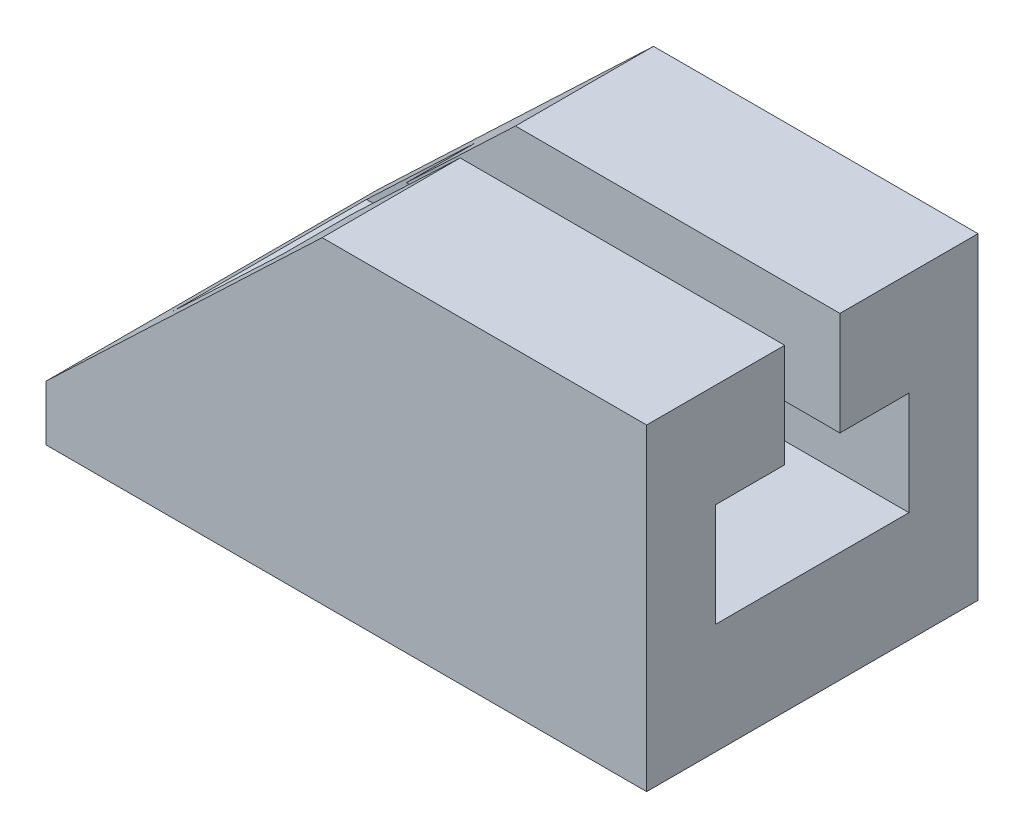
SolidWorks part; units mm, degrees
ref_plane "Front Plane" through (0, 0, 0) normal (0, 0, 1) x (1, 0, 0)
ref_plane "Top Plane" through (0, 0, 0) normal (0, 1, 0) x (1, 0, 0)
ref_plane "Right Plane" through (0, 0, 0) normal (1, 0, 0) x (0, 0, -1)
sketch "Sketch1" plane through (0, 0, 0) normal (0, 1, 0) x (1, 0, 0)
  line L1 (-43.5, -24) -> (43.5, -24)
  line L2 (-43.5, -24) -> (-43.5, 24)
  line L3 (-43.5, 24) -> (43.5, 24)
  line L4 (43.5, -24) -> (43.5, 24)
  line L5 (-43.5, -24) -> (43.5, 24) construction
  line L6 (-43.5, 24) -> (43.5, -24) construction
  point P0 (0, 0)
  dimension "D1" = 87
  dimension "D2" = 48
extrude "Boss-Extrude1" add sketch "Sketch1" along normal blind 46
sketch "Sketch2" plane through (0, 0, 0) normal (1, 0, 0) x (0, 0, -1)
  line L0 (0, 0) -> (0, 46) construction
  line L1 (-24, 46) -> (24, 46) construction
  line L2 (4, 31) -> (14, 31)
  line L4 (-4, 31) -> (-4, 46)
  line L5 (-4, 46) -> (4, 46)
  line L6 (4, 31) -> (4, 46)
  line L7 (-4, 31) -> (4, 46) construction
  line L8 (-4, 46) -> (4, 31) construction
  line L9 (-14, 16) -> (14, 16)
  line L10 (-14, 16) -> (-14, 31)
  line L11 (-14, 31) -> (-4, 31)
  line L12 (14, 16) -> (14, 31)
  line L13 (-14, 16) -> (14, 31) construction
  line L14 (-14, 31) -> (14, 16) construction
  point P5 (0, 38.5)
  point P10 (0, 23.5)
  dimension "D1" = 8
  dimension "D2" = 28
  dimension "D3" = 15
  dimension "D4" = 15
extrude "Cut-Extrude1" cut sketch "Sketch2" against normal through all both and the other way through all
sketch "Sketch3" plane through (0, 0, 0) normal (0, 0, 1) x (1, 0, 0)
  line L0 (-43.5, 46) -> (-43.5, 8)
  line L1 (-43.5, 46) -> (-43.5, 0) construction
  line L2 (-43.5, 8) -> (-3.5, 46)
  line L3 (-43.5, 46) -> (43.5, 46) construction
  line L4 (-3.5, 46) -> (-43.5, 46)
  line L5 (-43.5, 0) -> (43.5, 0) construction
  line L6 (43.5, 46) -> (43.5, 0) construction
  dimension "D1" = 8
  dimension "D2" = 47
extrude "Cut-Extrude2" cut sketch "Sketch3" against normal through all both and the other way through all
